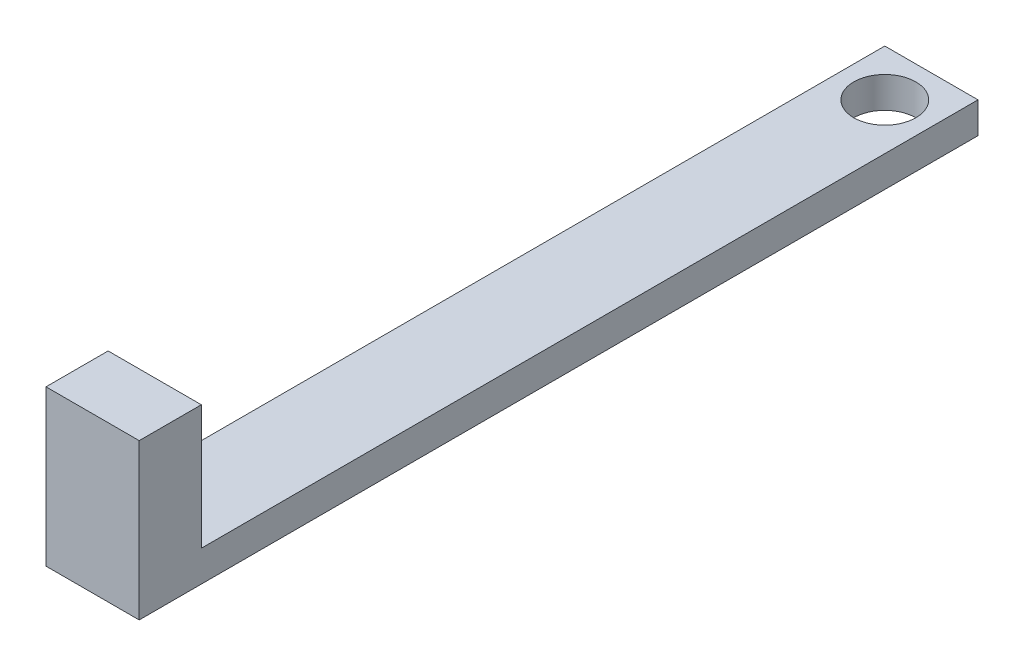
SolidWorks part; units mm, degrees
ref_plane "Front Plane" through (0, 0, 0) normal (0, 0, 1) x (1, 0, 0)
ref_plane "Top Plane" through (0, 0, 0) normal (0, 1, 0) x (1, 0, 0)
ref_plane "Right Plane" through (0, 0, 0) normal (1, 0, 0) x (0, 0, -1)
sketch "Sketch1" plane through (0, 0, 0) normal (1, 0, 0) x (0, 0, -1)
  line L0 (0, 40) -> (0, 0)
  line L1 (0, 0) -> (250, 0)
  line L2 (250, 0) -> (250, -10)
  line L3 (250, -10) -> (-20, -10)
  line L4 (-20, -10) -> (-20, 40)
  line L5 (-20, 40) -> (0, 40)
  dimension "D1" = 10
  dimension "D2" = 250
  dimension "D3" = 270
  dimension "D4" = 50
extrude "Boss-Extrude1" add sketch "Sketch1" along normal blind 30
sketch "Sketch2" plane through (0, 0, 0) normal (0, 1, 0) x (1, 0, 0)
  line L0 (0, 250) -> (0, 0) construction
  line L1 (30, 250) -> (0, 250) construction
  circle A0 centre (15, 235) radius 10
  dimension "D1" = 20
  dimension "D2" = 15
  dimension "D3" = 15
extrude "Cut-Extrude1" cut sketch "Sketch2" against normal blind 10
